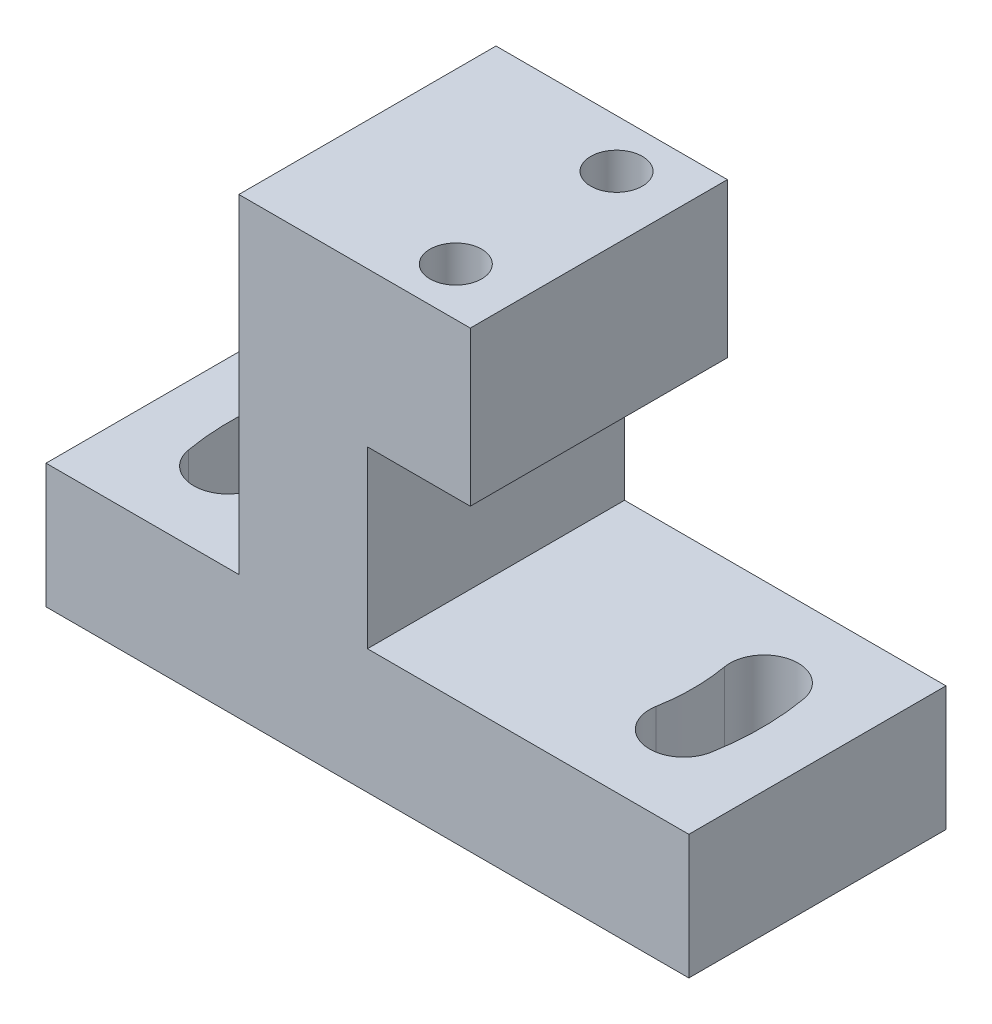
SolidWorks part; units mm, degrees
material "6061 Alloy"
ref_plane "Front Plane" through (0, 0, 0) normal (0, 0, 1) x (1, 0, 0)
ref_plane "Top Plane" through (0, 0, 0) normal (0, 1, 0) x (1, 0, 0)
ref_plane "Right Plane" through (0, 0, 0) normal (1, 0, 0) x (0, 0, -1)
sketch "Sketch1" plane through (0, 0, 0) normal (0, 0, 1) x (1, 0, 0)
  line L2 (-12.7, 44.8056) -> (10.16, 44.8056)
  line L3 (-31.75, 0) -> (31.75, 0)
  line L4 (-31.75, 0) -> (-31.75, 12.2936)
  line L5 (-31.75, 12.2936) -> (-12.7, 12.2936)
  line L6 (31.75, 0) -> (31.75, 12.2936)
  line L8 (-12.7, 12.2936) -> (-12.7, 44.8056)
  line L11 (12.7, 12.2936) -> (31.75, 12.2936)
  line L13 (10.16, 29.5656) -> (0, 29.5656)
  line L14 (10.16, 44.8056) -> (10.16, 29.5656)
  line L15 (12.7, 12.2936) -> (0, 12.2936)
  line L16 (0, 29.5656) -> (0, 12.2936)
  dimension "D1" = 12.7
  dimension "D3" = 63.5
  dimension "D5" = 12.2936
  dimension "D6" = 17.272
  dimension "D7" = 15.24
  dimension "D8" = 10.16
extrude "Extrude1" add sketch "Sketch1" along normal mid plane 25.4
sketch "Sketch2" plane through (0, 12.2936, 0) normal (0, 1, 0) x (-1, 0, 0)
  line L0 (-22.5127, 3.9696) -> (0, 0) construction
  line L1 (0, 0) -> (-22.5127, -3.9696) construction
  line L2 (0, 0) -> (-22.86, 0) construction
  line L3 (0, 22.86) -> (0, -22.86) construction
  circle A0 centre (-22.86, 0) radius 3.3782 construction
  circle A1 centre (0, 0) radius 22.86 construction
  arc A3 (-25.8396, -4.5562) -> (-19.1858, -3.383) centre (-22.5127, -3.9696) ccw
  arc A4 (-19.1858, 3.383) -> (-25.8396, 4.5562) centre (-22.5127, 3.9696) ccw
  arc A5 (-19.1858, 3.383) -> (-19.1858, -3.383) centre (0, 0) ccw
  arc A6 (-25.8396, 4.5562) -> (-25.8396, -4.5562) centre (0, 0) ccw
  dimension "D2" = 45.72
  dimension "D1" = 6.7564
  dimension "D3" = 20
extrude "Arc mounting slot I" cut sketch "Sketch2" against normal through all
mirror "Arc mounting slot II" about plane through (0, 0, 0) normal (1, 0, 0) of "Arc mounting slot I"
hole_wizard "Clamping screw holes" positions "Sketch5" profile "Sketch4" tap size "1/4-20" standard "Ansi Inch"
sketch "Sketch5" plane through (0, 44.8056, 0) normal (0, 1, 0) x (-1, 0, 0)
  line L0 (0, 0) -> (-3.9688, 0) construction
  line L1 (-3.9688, 7.9375) -> (-3.9688, -7.9375) construction
  point P0 (-3.9688, -7.9375)
  point P1 (-3.9688, 7.9375)
  dimension "D1" = 15.875
  dimension "D2" = 3.9688
cosmetic thread "Hole Thread1" parameters "D1"=15.24, "D2"=6.35
cosmetic thread "Hole Thread2" parameters "D1"=15.24, "D2"=6.35
sketch "Sketch4" plane through (3.9688, 44.8056, -7.9375) normal (1, 0, 0) x (0, 0, 1)
  line L0 (0, 0) -> (0, 16.7738)
  line L1 (0, 16.7738) -> (2.5527, 15.24)
  line L2 (2.5527, 15.24) -> (2.5527, 0)
  line L5 (2.5527, 0) -> (0, 0)
  line L10 (0, 16.7738) -> (-2.5527, 15.24) construction
  line L11 (0, -6.35) -> (0, 107.95) construction
  dimension "Tap Drill Dia." = 5.1054
  dimension "Tap Drill Depth" = 15.24
  dimension "Drill Angle" = 118
sketch "Sketch6" plane through (0, 0, 0) normal (0, 0, 1) x (1, 0, 0)
  line L0 (31.75, 0) -> (31.75, 20.2413) construction
  line L3 (2.8297, 15.1233) -> (0, 15.1233)
  line L4 (2.8297, 15.1233) -> (2.8297, 12.2936)
  line L5 (2.8297, 12.2936) -> (0, 12.2936)
  line L6 (0, 15.1233) -> (0, 12.2936)
  dimension "D1" = 20.2413
  dimension "D2" = 2.8297
